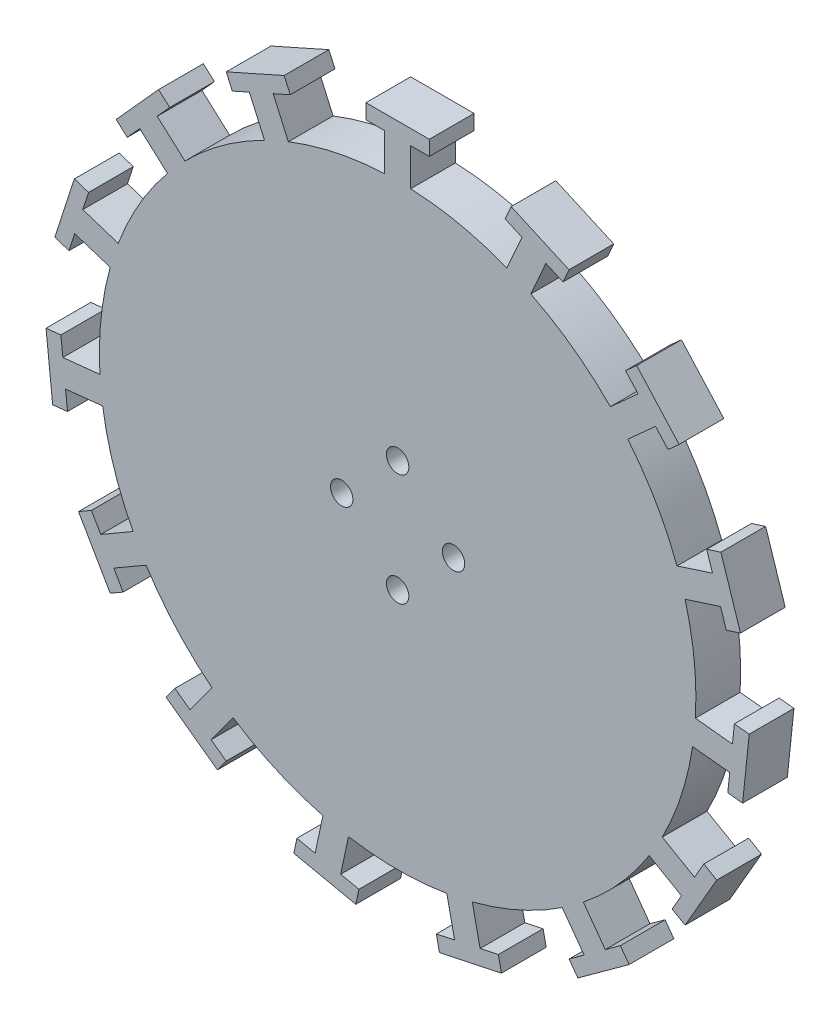
SolidWorks part; units mm, degrees
ref_plane "Front Plane" through (0, 0, 0) normal (0, 0, 1) x (1, 0, 0)
ref_plane "Top Plane" through (0, 0, 0) normal (0, 1, 0) x (1, 0, 0)
ref_plane "Right Plane" through (0, 0, 0) normal (1, 0, 0) x (0, 0, -1)
sketch "Sketch1" plane through (0, 0, 0) normal (0, 0, 1) x (1, 0, 0)
  circle A0 centre (0, 0) radius 40
  dimension "D1" = 80
extrude "Boss-Extrude1" add sketch "Sketch1" along normal blind 2
sketch "Sketch6" plane through (0, 0, 0) normal (0, 0, 1) x (1, 0, 0)
  line L0 (-1.75, 39.9617) -> (-1.75, 44.9617)
  line L1 (0, 37.6165) -> (0, 55.5597) construction
  line L2 (1.75, 39.9617) -> (1.75, 44.9617)
  line L3 (-1.75, 44.9617) -> (-4.25, 44.9617)
  line L4 (-4.25, 44.9617) -> (-4.25, 46.9617)
  line L5 (-4.25, 46.9617) -> (4.25, 46.9617)
  line L6 (4.25, 46.9617) -> (4.25, 44.9617)
  line L7 (4.25, 44.9617) -> (1.75, 44.9617)
  circle A0 centre (0, 0) radius 40 construction
  circle A2 centre (0, 0) radius 40
  arc A3 (-1.75, 39.9617) -> (1.75, 39.9617) centre (0, 0) ccw
  dimension "D1" = 3.5
  dimension "D2" = 5
  dimension "D3" = 2
  dimension "D4" = 2.5
  dimension "D5" = 0
extrude "Boss-Extrude2" add sketch "Sketch6" along normal blind 6
pattern_circular "CirPattern1" count 15 over 360 about axis through (0, 0, 0) along (0, 0, 1) of "Boss-Extrude2"
sketch "Sketch4" plane through (0, 0, 2) normal (0, 0, 1) x (1, 0, 0)
  line L0 (0, -3.3) -> (0, 3.3) construction
  circle A0 centre (0, 7.5) radius 1.5
  circle A4 centre (7.5, 0) radius 1.5
  circle A5 centre (0, -7.5) radius 1.5
  circle A6 centre (-7.5, 0) radius 1.5
  point P15 (0, 0)
  dimension "D1" = 3
  dimension "D2" = 7.5
  dimension "D3" = 4
extrude "Cut-Extrude2" cut sketch "Sketch4" against normal mid plane 20
equation "\"diameter\"=80"
equation "\"D1@Plane2\"=\"diameter\"/2"
